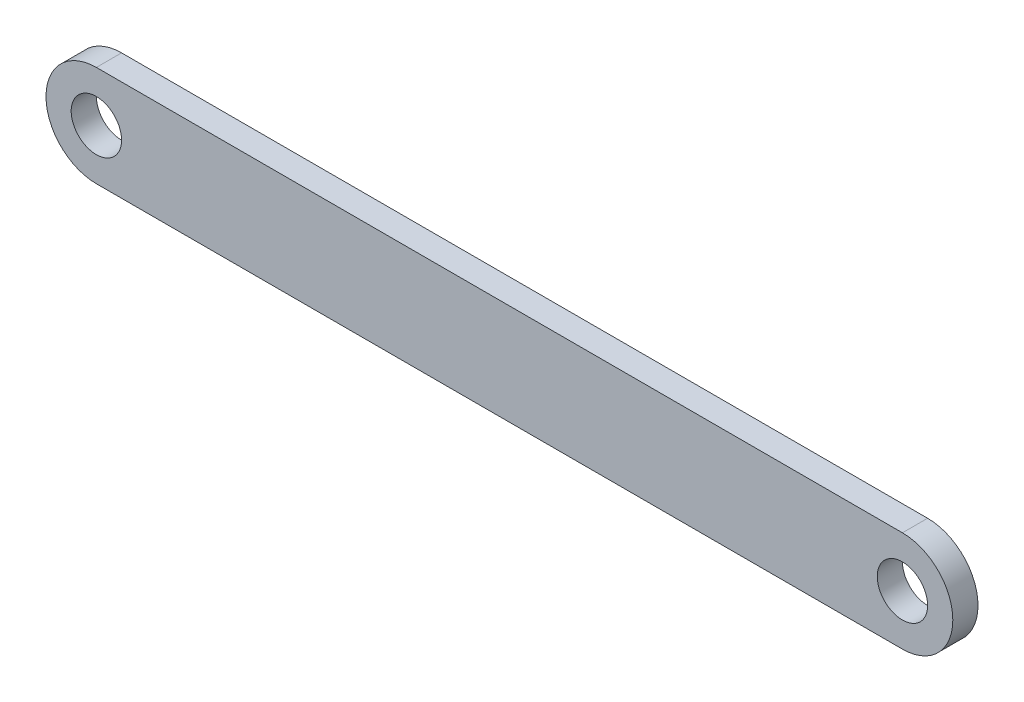
SolidWorks part; units mm, degrees
ref_plane "Front Plane" through (0, 0, 0) normal (0, 0, 1) x (1, 0, 0)
ref_plane "Top Plane" through (0, 0, 0) normal (0, 1, 0) x (1, 0, 0)
ref_plane "Right Plane" through (0, 0, 0) normal (1, 0, 0) x (0, 0, -1)
sketch "Sketch2" plane through (0, 0, 0) normal (0, 0, 1) x (1, 0, 0)
  line L7 (-50.8, 0) -> (50.8, 0) construction
  line L8 (-50.8, 6.35) -> (50.8, 6.35)
  line L9 (-50.8, -6.35) -> (50.8, -6.35)
  arc A2 (-50.8, 6.35) -> (-50.8, -6.35) centre (-50.8, 0) ccw
  arc A3 (50.8, -6.35) -> (50.8, 6.35) centre (50.8, 0) ccw
  point P3 (0, 0)
  dimension "D1" = 12.7
  dimension "D2" = 101.6
  dimension "D3" = 0
  dimension "D4" = 0
extrude "Boss-Extrude1" add sketch "Sketch2" along normal blind 3.175
sketch "Sketch3" plane through (0, 0, 3.175) normal (0, 0, 1) x (1, 0, 0)
  line L0 (0, 0) -> (-57.15, 0) construction
  line L1 (-50.8, 6.35) -> (-50.8, -6.35) construction
  line L2 (0, 0) -> (0, -6.35) construction
  line L3 (-50.8, -6.35) -> (50.8, -6.35) construction
  line L4 (0, -6.35) -> (0, 6.35) construction
  line L5 (50.8, 6.35) -> (-50.8, 6.35) construction
  arc A0 (-50.8, 6.35) -> (-50.8, -6.35) centre (-50.8, 0) ccw construction
  circle A1 centre (-50.8, 0) radius 3.175
  circle A2 centre (50.8, 0) radius 3.175
  dimension "D1" = 6.35
extrude "Cut-Extrude1" cut sketch "Sketch3" against normal through all
